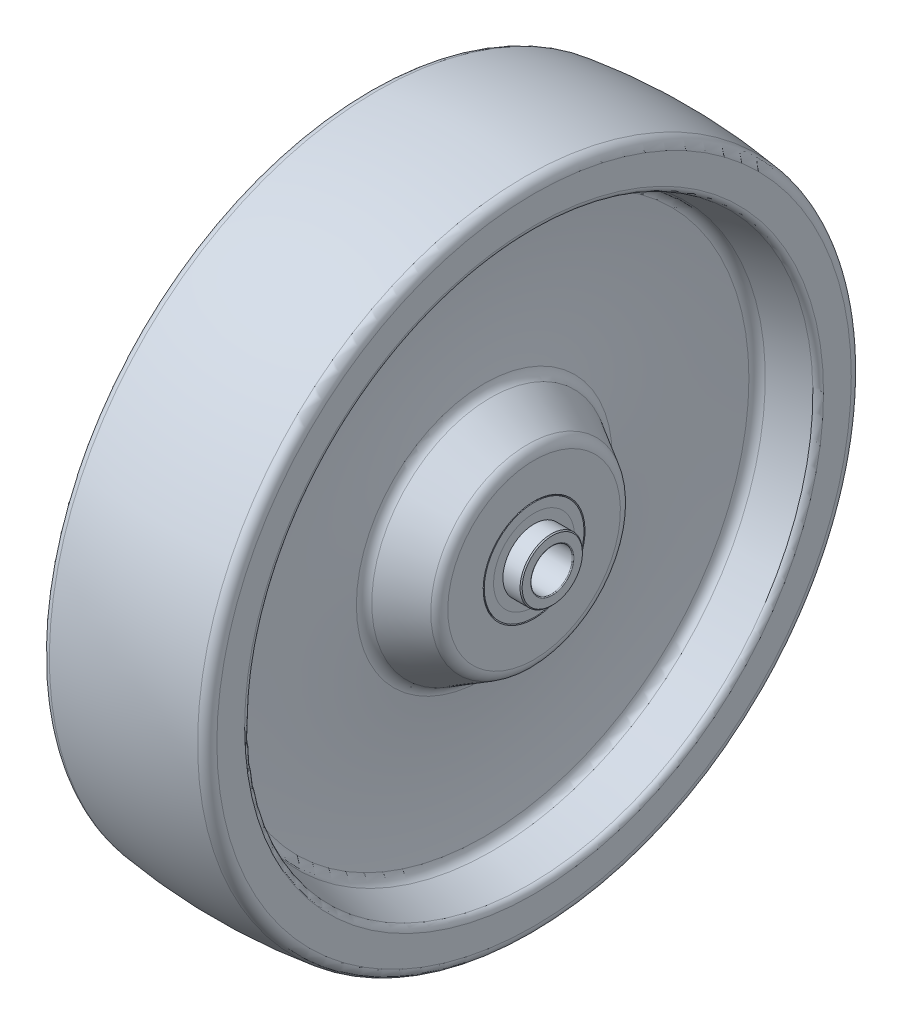
SolidWorks part; units mm, degrees
ref_plane "Front Plane" through (0, 0, 0) normal (0, 0, 1) x (1, 0, 0)
ref_plane "Top Plane" through (0, 0, 0) normal (0, 1, 0) x (1, 0, 0)
ref_plane "Right Plane" through (0, 0, 0) normal (1, 0, 0) x (0, 0, -1)
sketch "Sketch1" plane through (0, 0, 0) normal (1, 0, 0) x (0, 0, -1)
  line L0 (0, 101.6) -> (0, -101.6) construction
  line L1 (-101.6, 0) -> (101.6, 0) construction
  circle A1 centre (0, 0) radius 101.6 construction
  circle A2 centre (0, 0) radius 6.35
  circle A3 centre (0, 0) radius 9.525
  point P2 (0, -15.24)
  point P4 (0, 15.24)
  point P5 (0, 0)
  point P10 (0, 6.35)
  point P11 (0, -6.35)
  point P14 (0, -28.575)
  point P17 (0, 28.575)
  point P18 (0, 9.525)
  dimension "Wheel Diameter" = 203.2
  dimension "Bearing ID" = 19.05
  dimension "For Axle Diameter" = 12.7
  dimension "Bearing OD" = 30.48
  dimension "D1" = 57.15
sketch "Sketch2" plane through (0, 0, 0) normal (0, 0, 1) x (1, 0, 0)
  line L0 (-30.9562, 0) -> (30.9562, 0) construction
  line L1 (-30.9562, 28.575) -> (30.9562, 28.575) construction
  line L2 (-25.4, 101.6) -> (25.4, 101.6) construction
  point P3 (0, 0)
  point P8 (0, 101.6)
  point P12 (0, 28.575)
  dimension "Hub Length" = 61.9125
  dimension "Wheel Width" = 50.8
sketch "Sketch3" plane through (0, 0, 0) normal (0, 0, 1) x (1, 0, 0)
  line L0 (-30.9562, 0) -> (30.9562, 0) construction
  line L1 (-25.4, 99.695) -> (-25.4, 88.4568)
  line L2 (0, -101.6) -> (0, 101.6) construction
  line L3 (0, -101.6) -> (0, 101.6) construction
  line L4 (-30.9562, 0) -> (30.9562, 0) construction
  line L5 (25.0825, 15.24) -> (-25.0825, 15.24)
  line L6 (-30.9562, 28.575) -> (30.9562, 28.575) construction
  line L7 (-10.16, 39.5735) -> (-10.16, 80.4752) construction
  line L11 (-25.4, 15.5575) -> (-25.4, 26.3753)
  line L12 (-25.4, 15.5575) -> (-25.0825, 15.24)
  line L13 (25.4, 15.5575) -> (25.0825, 15.24)
  line L16 (25.4, 99.695) -> (25.4, 88.4568)
  line L17 (-25.4, 101.6) -> (25.4, 101.6) construction
  line L18 (25.4, 15.5575) -> (25.4, 26.3753)
  line L19 (-23.495, 29.6749) -> (-12.065, 36.274)
  line L21 (-12.5132, 83.542) -> (-23.9881, 86.6167)
  line L22 (12.5132, 83.542) -> (23.9881, 86.6167)
  line L23 (10.16, 39.5735) -> (10.16, 80.4752) construction
  line L24 (23.495, 29.6749) -> (12.065, 36.274)
  arc A15 (-25.4, 99.695) -> (25.4, 99.695) centre (0, -68.6858) cw
  arc A24 (-12.5132, 83.542) -> (-10.16, 80.4752) centre (-13.335, 80.4752) cw construction
  arc A25 (-12.065, 36.274) -> (-10.16, 39.5735) centre (-13.97, 39.5735) ccw construction
  arc A26 (12.5132, 83.542) -> (10.16, 80.4752) centre (13.335, 80.4752) ccw construction
  arc A27 (12.065, 36.274) -> (10.16, 39.5735) centre (13.97, 39.5735) cw construction
  arc A28 (-10.1893, 39.1017) -> (-10.1843, 80.8676) centre (-177.6776, 60.0046) ccw
  arc A29 (10.1893, 39.1017) -> (10.1843, 80.8676) centre (177.6776, 60.0046) cw
  arc A30 (10.1843, 80.8676) -> (12.5132, 83.542) centre (13.335, 80.4752) cw
  arc A31 (12.065, 36.274) -> (10.1893, 39.1017) centre (13.97, 39.5735) cw
  arc A32 (-12.065, 36.274) -> (-10.1893, 39.1017) centre (-13.97, 39.5735) ccw
  arc A33 (-12.5132, 83.542) -> (-10.1843, 80.8676) centre (-13.335, 80.4752) cw
  arc A34 (-25.4, 26.3753) -> (-23.495, 29.6749) centre (-21.59, 26.3753) cw
  arc A35 (23.495, 29.6749) -> (25.4, 26.3753) centre (21.59, 26.3753) cw
  arc A36 (-23.9881, 86.6167) -> (-25.4, 88.4568) centre (-23.495, 88.4568) cw
  arc A37 (23.9881, 86.6167) -> (25.4, 88.4568) centre (23.495, 88.4568) ccw
  point P4 (0, 101.6)
  point P14 (-10.16, 37.3738)
  point P35 (-8.89, 59.9845)
  point P50 (-25.4, 28.575)
  point P53 (25.4, 28.575)
  point P56 (-25.4, 86.995)
  point P59 (25.4, 86.995)
  dimension "D10" = 3.175
  dimension "D11" = 3.81
  dimension "D13" = 3.81
  dimension "D14" = 1.905
  dimension "D7" = 45
  dimension "D8" = 0.3175
  dimension "D2" = 30
  dimension "D6" = 10.16
  dimension "D5" = 74.7476
  dimension "D1" = 173.99
  dimension "D4" = 12.7
  dimension "D9" = 1.905
  dimension "D3" = 15
  dimension "D12" = 17.78
revolve "Revolve1" add sketch "Sketch3" angle 360 about L4
sketch "Sketch4" plane through (0, 0, 0) normal (0, 0, 1) x (1, 0, 0)
  line L0 (25.4, 15.24) -> (-25.4, 15.24)
  line L2 (-25.4, 11.43) -> (-15.875, 11.43) construction
  line L5 (-25.4, 9.525) -> (-15.875, 9.525) construction
  line L6 (0, -6.35) -> (0, 6.35) construction
  line L7 (25.4, 9.525) -> (-25.4, 9.525) construction
  line L10 (-25.4, 9.525) -> (-25.4, 11.43) construction
  line L11 (-25.4, 11.43) -> (25.4, 11.43) construction
  line L13 (-30.9562, 0) -> (30.9562, 0) construction
  line L14 (-30.9562, 0) -> (30.9562, 0) construction
  line L16 (0, 0) -> (0, 9.525) construction
  line L17 (0, -101.6) -> (0, 101.6) construction
  line L19 (25.4, 11.43) -> (25.4, 9.525) construction
  line L20 (-25.4, 15.24) -> (-25.4, 12.3825)
  line L21 (-25.4, 12.3825) -> (25.4, 12.3825)
  line L22 (0, 9.525) -> (0, 15.24) construction
  line L23 (25.4, 12.3825) -> (25.4, 15.24)
  line L27 (-15.875, 11.43) -> (-15.875, 9.525) construction
  line L28 (15.875, 11.43) -> (15.875, 9.525) construction
  line L29 (15.875, 9.525) -> (25.4, 9.525) construction
  line L30 (15.875, 11.43) -> (25.4, 11.43) construction
  line L31 (0, -9.525) -> (0, 9.525) construction
  point P3 (0, 12.3825)
  point P9 (0, 15.24)
  dimension "D2" = 1.905
  dimension "D7" = 9.525
revolve "Revolve2" add sketch "Sketch4" angle 360 about L14
sketch "Sketch7" plane through (0, 0, 0) normal (0, 0, 1) x (1, 0, 0)
  line L8 (-30.9562, 0) -> (30.9562, 0) construction
  line L9 (-30.9562, 0) -> (30.9562, 0) construction
  line L10 (-25.4, 9.525) -> (25.4, 9.525)
  line L11 (-25.4, 9.525) -> (-25.4, 12.3825)
  line L12 (-25.4, 12.3825) -> (25.4, 12.3825)
  line L13 (25.4, 9.525) -> (25.4, 12.3825)
revolve "Revolve3" add sketch "Sketch7" angle 360 about L9
sketch "Sketch8" plane through (0, 0, 0) normal (0, 0, 1) x (1, 0, 0)
  line L0 (-30.9562, 0) -> (30.9562, 0) construction
  line L1 (-30.9562, 0) -> (30.9562, 0) construction
  line L4 (30.9562, 6.604) -> (30.9562, 9.2075)
  line L5 (-30.6387, 9.525) -> (30.6387, 9.525)
  line L6 (-30.6387, 9.525) -> (-30.9562, 9.2075)
  line L7 (-30.9562, 6.604) -> (-30.9562, 9.2075)
  line L9 (-30.7022, 6.35) -> (30.7022, 6.35)
  line L13 (30.6387, 9.525) -> (30.9562, 9.2075)
  arc A0 (30.7022, 6.35) -> (30.9562, 6.604) centre (30.7022, 6.604) ccw
  arc A1 (-30.7022, 6.35) -> (-30.9562, 6.604) centre (-30.7022, 6.604) cw
  point P14 (0, 9.525)
  point P15 (0, 6.35)
  point P17 (30.9562, 6.35)
  dimension "D3" = 0.254
  dimension "D1" = 45
  dimension "D2" = 0.3175
revolve "Revolve4" add sketch "Sketch8" angle 360 about L1
sketch "Sketch9" plane through (0, 0, 0) normal (0, 0, 1) x (1, 0, 0)
  line L0 (0, -6.35) -> (0, 6.35) construction
  circle A0 centre (0, 0) radius 2.432
  dimension "D1" = 4.8641
extrude "Cut-Extrude1" cut sketch "Sketch9" against normal through all both and the other way through all
fillet "Fillet1" radius 3.175 2 edges at (25.4, -99.695, 0) (-25.4, -99.695, 0)
sketch "Sketch5" plane through (0, 0, 0) normal (0, 0, 1) x (1, 0, 0)
  line L1 (30.7022, 6.35) -> (-30.7022, 6.35) construction
  line L8 (-30.9562, 0) -> (30.9562, 0) construction
  line L9 (-30.9562, 0) -> (30.9562, 0) construction
  line L12 (30.7022, 6.35) -> (-30.7022, 6.35)
  line L13 (30.7022, -6.35) -> (-30.7022, -6.35)
equation "\"D8@Sketch3\"=\"For Axle Diameter@Sketch1\" * 0.025"
equation "\"D6@Sketch3\"=\"Wheel Width@Sketch2\"*0.2"
equation "\"D4@Sketch3\"=\"Wheel Diameter@Sketch1\"*0.0625"
equation "\"D2@Sketch4\"=\"Bearing OD@Sketch1\"*0.0625"
equation "\"D12@Sketch3\"=\"Wheel Width@Sketch2\"*0.35"
equation "\"D13@Sketch3\"=\"Wheel Diameter@Sketch1\"*0.01875"
equation "\"D14@Sketch3\"=\"D13@Sketch3\"/2"
